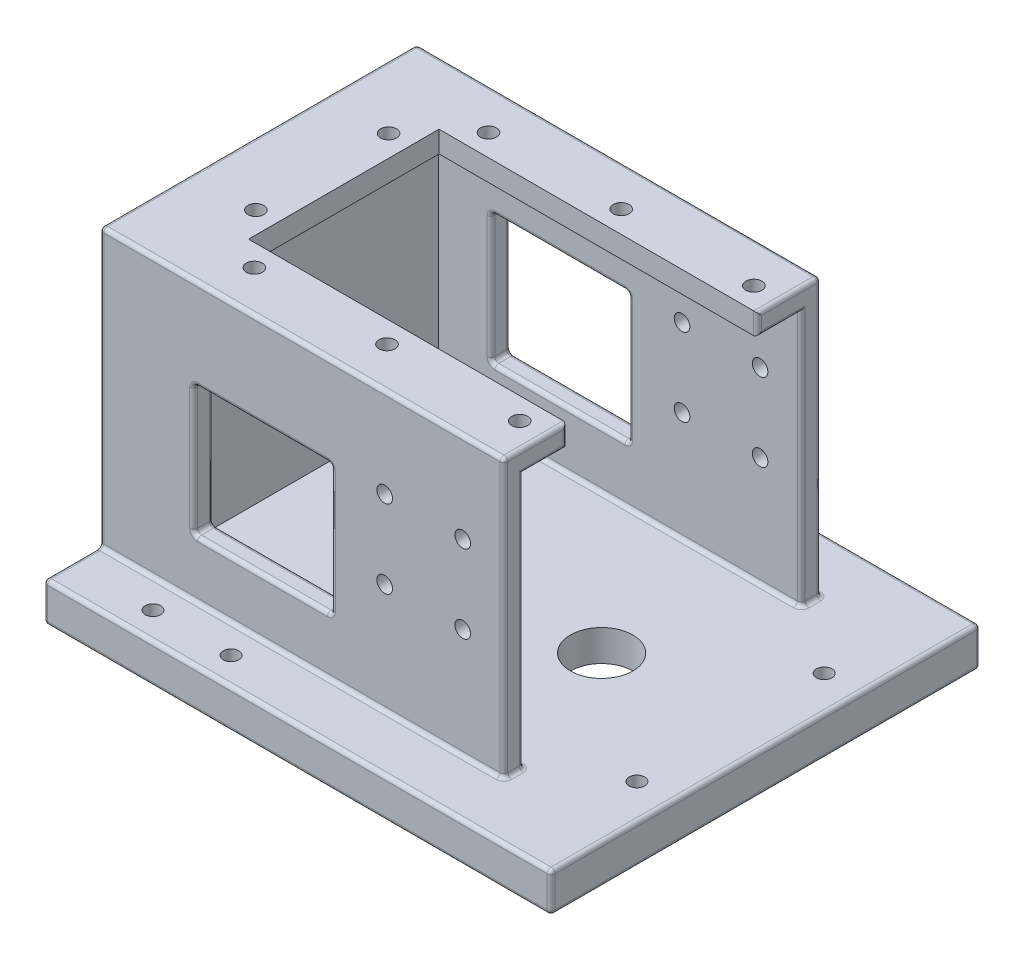
SolidWorks part; units mm, degrees
ref_plane "Front Plane" through (0, 0, 0) normal (0, 0, 1) x (1, 0, 0)
ref_plane "Top Plane" through (0, 0, 0) normal (0, 1, 0) x (1, 0, 0)
ref_plane "Right Plane" through (0, 0, 0) normal (1, 0, 0) x (0, 0, -1)
sketch "Sketch1" plane through (0, 298.2839, 0) normal (0, 1, 0) x (1, 0, 0)
  line L0 (0, 0) -> (-29.3281, 0) construction
  line L1 (-43.9857, 27.5) -> (21.0143, 27.5)
  line L2 (-43.9857, 27.5) -> (-43.9857, -27.5)
  line L3 (-43.9857, -27.5) -> (21.0143, -27.5)
  line L4 (21.0143, 27.5) -> (21.0143, -27.5)
  circle A1 centre (0, 0) radius 4
  circle A2 centre (0, 0) radius 4 construction
  dimension "D1" = 55
  dimension "D2" = 65
extrude "Boss-Extrude1" add sketch "Sketch1" along normal blind 5
sketch "Sketch5" plane through (0, 298.2839, 0) normal (0, -1, 0) x (1, 0, 0)
  circle A0 centre (0, 0) radius 12.5
  dimension "D1" = 25
extrude "Cut-Extrude3" cut sketch "Sketch5" against normal blind 1
sketch "Sketch6" plane through (0, 303.2839, 0) normal (0, 1, 0) x (1, 0, 0)
  line L0 (7.7697, 17.8) -> (7.7697, 20.3)
  line L1 (7.7697, 20.3) -> (-43.9857, 20.3)
  line L2 (-43.9857, 27.5) -> (-43.9857, -27.5) construction
  line L3 (-43.9857, 20.3) -> (-43.9857, -20.3)
  line L4 (-43.9857, -20.3) -> (7.7697, -20.3)
  line L5 (7.7697, -20.3) -> (7.7697, -17.8)
  line L6 (7.7697, 17.8) -> (-38.6893, 17.8)
  line L7 (-38.6893, 17.8) -> (-38.6893, -17.8)
  line L8 (-38.6893, -17.8) -> (7.7697, -17.8)
  line L9 (0, 0) -> (-23.7296, 0) construction
  dimension "D1" = 2.5
  dimension "D2" = 2.5
  dimension "D4" = 35.6
extrude "Boss-Extrude2" add sketch "Sketch6" along normal up to surface (35.5 mm away)
sketch "Sketch11" plane through (0, 338.7839, 0) normal (0, 1, 0) x (1, 0, 0)
  line L0 (7.7697, 17.8) -> (7.7697, 12.2)
  line L2 (7.7697, 12.2) -> (-33.0356, 12.2)
  line L3 (-33.0356, 12.2) -> (-33.0356, -12.2)
  line L4 (-33.0356, -12.2) -> (7.7697, -12.2)
  line L6 (7.7697, -12.2) -> (7.7697, -17.8)
  line L7 (7.7697, -17.8) -> (-38.6893, -17.8) construction
  line L8 (7.7697, -20.3) -> (7.7697, -17.8) construction
  line L9 (7.7697, 17.8) -> (-40.3738, 17.8)
  line L10 (-40.3738, 17.8) -> (-40.3738, -17.8)
  line L11 (-40.3738, -17.8) -> (7.7697, -17.8)
  point P9 (0, 0)
  point P17 (0, 0)
extrude "Boss-Extrude4" add sketch "Sketch11" against normal blind 2.75
sketch "Sketch12" plane through (0, 338.7839, 0) normal (0, 1, 0) x (1, 0, 0)
  circle A8 centre (4.5, -15) radius 1.025
  circle A9 centre (-12.5, -15) radius 1.025
  circle A10 centre (-29.5, -15) radius 1.025
  circle A11 centre (-35.8, -8.5) radius 1.025
  circle A12 centre (-35.8, 8.5) radius 1.025
  circle A13 centre (-29.5, 15) radius 1.025
  circle A14 centre (4.5, 15) radius 1.025
  circle A15 centre (-12.5, 15) radius 1.025
extrude "Cut-Extrude4" cut sketch "Sketch12" against normal blind 2.75
sketch "Sketch13" plane through (0, 0, 20.3) normal (0, 0, 1) x (1, 0, 0)
  line L6 (-31.975, 310.5339) -> (-14.3314, 310.5339)
  line L7 (-31.975, 310.5339) -> (-31.975, 327.2039)
  line L8 (-31.975, 327.2039) -> (-14.3314, 327.2039)
  line L9 (-14.3314, 310.5339) -> (-14.3314, 327.2039)
  point P4 (0, 0)
extrude "Cut-Extrude6" cut sketch "Sketch13" against normal through all
fillet "Fillet1" radius 0.5 59 edges at (-18.108, 303.2839, -20.3) (-15.4598, 303.2839, -17.8) (-15.4598, 303.2839, 17.8) (-18.108, 303.2839, 20.3) (-14.3314, 318.8689, -17.8) (-31.975, 318.8689, -17.8) (-31.975, 318.8689, -20.3) (-14.3314, 318.8689, -20.3) (-23.1532, 327.2039, 17.8) (-23.1532, 310.5339, 17.8) (-23.1532, 310.5339, 20.3) (-23.1532, 327.2039, 20.3) (7.7697, 321.0339, -20.3) (7.7697, 303.2839, -19.05) (7.7697, 319.6589, -17.8) (7.7697, 336.0339, -15) (7.7697, 337.4089, -12.2) (7.7697, 338.7839, -16.25) (7.7697, 337.4089, 12.2) (7.7697, 336.0339, 15) (7.7697, 319.6589, 17.8) (7.7697, 303.2839, 19.05) (7.7697, 321.0339, 20.3) (7.7697, 338.7839, 16.25) (-11.4857, 303.2839, 27.5) (21.0143, 300.7839, 27.5) (-11.4857, 298.2839, 27.5) (-43.9857, 303.2839, -23.9) (-43.9857, 321.0339, -20.3) (-43.9857, 338.7839, 0) (-43.9857, 321.0339, 20.3) (-43.9857, 303.2839, 23.9) (-43.9857, 300.7839, 27.5) (-43.9857, 298.2839, 0) (21.0143, 300.7839, -27.5) (-11.4857, 303.2839, -27.5) (-43.9857, 300.7839, -27.5) (-11.4857, 298.2839, -27.5) (-23.1532, 327.2039, -17.8) (-14.3314, 327.2039, -19.05) (-23.1532, 327.2039, -20.3) (-31.975, 327.2039, -19.05) (-23.1532, 310.5339, -17.8) (-31.975, 310.5339, -19.05) (-23.1532, 310.5339, -20.3) (-14.3314, 310.5339, -19.05) (-14.3314, 318.8689, 17.8) (-14.3314, 327.2039, 19.05) (-14.3314, 318.8689, 20.3) (-14.3314, 310.5339, 19.05) (-31.975, 318.8689, 17.8) (-31.975, 310.5339, 19.05) (-31.975, 318.8689, 20.3) (-31.975, 327.2039, 19.05) (-18.108, 338.7839, 20.3) (-18.108, 338.7839, -20.3) (0, 299.2839, -12.5) (21.0143, 303.2839, 0) (21.0143, 298.2839, 0)
sketch "Sketch14" plane through (0, 0, 20.3) normal (0, 0, 1) x (1, 0, 0)
  circle A0 centre (-7.5, 327.3068) radius 1
  circle A1 centre (2.5, 327.3068) radius 1
  circle A2 centre (2.5, 317.3068) radius 1
  circle A3 centre (-7.5, 317.3068) radius 1
extrude "Cut-Extrude7" cut sketch "Sketch14" against normal through all
sketch "Sketch15" plane through (0, 303.2839, 0) normal (0, 1, 0) x (1, 0, 0)
  line L0 (20.5143, 27) -> (-43.4857, 27) construction
  line L1 (-43.4857, 27) -> (-43.4857, 20.8) construction
  line L2 (-43.4857, -20.8) -> (-43.4857, -27) construction
  line L3 (-43.4857, -27) -> (20.5143, -27) construction
  line L4 (20.5143, -27) -> (20.5143, 27) construction
  circle A0 centre (-33.4857, 24) radius 1
  circle A1 centre (-23.4857, 24) radius 1
  circle A2 centre (-33.4857, -24) radius 1
  circle A3 centre (-23.4857, -24) radius 1
  circle A4 centre (16.5143, 12) radius 1
  circle A5 centre (16.5143, -12) radius 1
  point P22 (0, 0)
  dimension "D1" = 2
  dimension "D4" = 2
  dimension "D2" = 3
  dimension "D3" = 10
  dimension "D5" = 10
  dimension "D6" = 10
  dimension "D7" = 10
  dimension "D8" = 3
  dimension "D9" = 4
  dimension "D10" = 15
  dimension "D11" = 15
extrude "Cut-Extrude8" cut sketch "Sketch15" against normal through all
